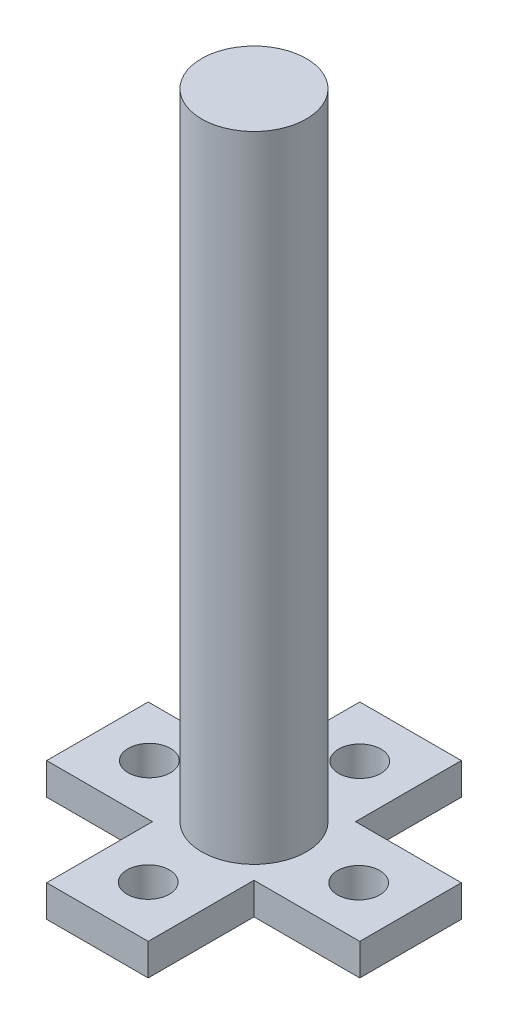
SolidWorks part; units mm, degrees
ref_plane "前视基准面" through (0, 0, 0) normal (0, 0, 1) x (1, 0, 0)
ref_plane "上视基准面" through (0, 0, 0) normal (0, 1, 0) x (1, 0, 0)
ref_plane "右视基准面" through (0, 0, 0) normal (1, 0, 0) x (0, 0, -1)
other "Configuration Table"
sketch "草图1" plane through (0, 0, 0) normal (0, 1, 0) x (1, 0, 0)
  line L0 (-14.9378, 4.9391) -> (35717.0744, -34969.6704) construction
  line L5 (-15, -5) -> (15, 5) construction
  line L6 (-15, 5) -> (15, -5) construction
  line L11 (-5, -15) -> (5, 15) construction
  line L12 (-5, 15) -> (5, -15) construction
  line L13 (-5, 5) -> (-35360.3391, -35350.3391) construction
  line L14 (5, 5) -> (35360.3391, -35350.3391) construction
  line L15 (5, -5) -> (-35350.3391, -35360.3391) construction
  line L16 (-4.8, 14.8) -> (4.8, 14.8)
  line L17 (4.8, -14.8) -> (4.8, 14.8)
  line L18 (-4.8, -14.8) -> (4.8, -14.8)
  line L19 (-4.8, -14.8) -> (-4.8, 14.8)
  line L20 (-14.8, 4.8) -> (14.8, 4.8)
  line L21 (14.8, -4.8) -> (14.8, 4.8)
  line L22 (-14.8, -4.8) -> (14.8, -4.8)
  line L23 (-14.8, -4.8) -> (-14.8, 4.8)
  circle A0 centre (0, 0) radius 4
  circle A1 centre (-9.9464, 0.0536) radius 2
  circle A2 centre (0.0536, 9.9464) radius 2
  circle A3 centre (9.9464, -0.0536) radius 2
  circle A4 centre (-0.0536, -9.9464) radius 2
  point P0 (0, 0)
  point P6 (0, 0)
  dimension "D5" = 8
  dimension "D6" = 4
  dimension "D1" = 30
  dimension "D2" = 30
  dimension "D3" = 10
  dimension "D4" = 10
  dimension "D7" = 4
extrude "凸台-拉伸2" add sketch "草图1" along normal blind 3 contours L23 L22 L19 L20 A1 | L22 L19 L18 L17 A4 | L19 L22 L17 L20 A0 | L17 L22 L21 L20 A3 | L19 L20 L17 L16 A2 | A0
sketch "草图2" plane through (0, 3, 0) normal (0, 1, 0) x (1, 0, 0)
  circle A0 centre (0, 0) radius 3.95
  dimension "D1" = 7.9
extrude "凸台-拉伸3" add sketch "草图2" along normal blind 120
sketch "草图3" plane through (0, 123, 0) normal (0, 1, 0) x (1, 0, 0)
  circle A0 centre (0, 0) radius 3.95
extrude "切除-拉伸1" cut sketch "草图3" against normal blind 60
sketch "草图4" plane through (0, 63, 0) normal (0, 1, 0) x (1, 0, 0)
  circle A0 centre (0, 0) radius 4.95
  dimension "D1" = 9.9
extrude "凸台-拉伸4" add sketch "草图4" against normal blind 60
